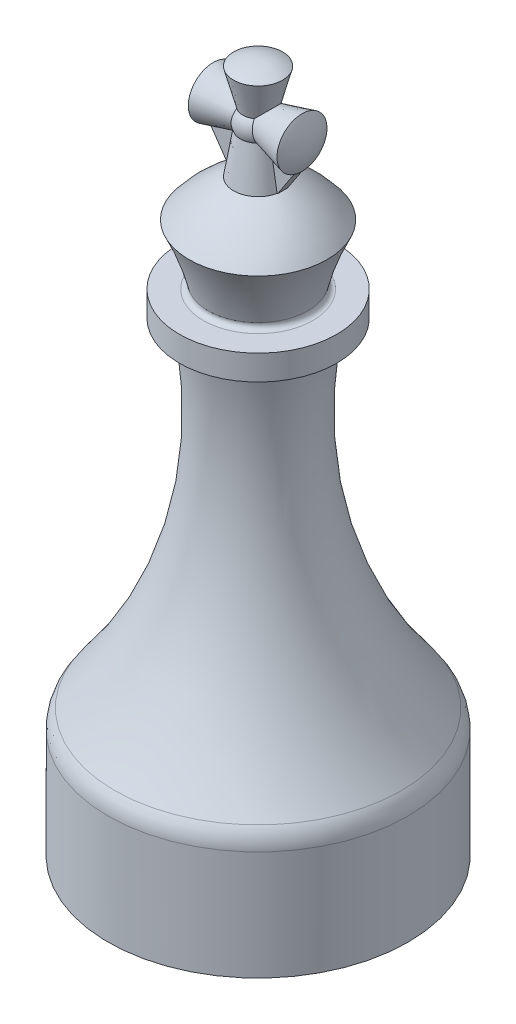
SolidWorks part; units mm, degrees
other "Camera1"
ref_plane "Front Plane" through (0, 0, 0) normal (0, 0, 1) x (1, 0, 0)
ref_plane "Top Plane" through (0, 0, 0) normal (0, 1, 0) x (1, 0, 0)
ref_plane "Right Plane" through (0, 0, 0) normal (1, 0, 0) x (0, 0, -1)
sketch "Sketch3" plane through (0, 0, 0) normal (0, 0, 1) x (1, 0, 0)
  line L0 (31.0622, 0) -> (31.0622, 75)
  line L1 (31.0622, 75) -> (-18.2567, 75)
  line L2 (0, 0) -> (31.0622, 0) construction
  dimension "D1" = 75
sketch "Sketch1" plane through (0, 0, 0) normal (0, 0, 1) x (1, 0, 0)
  line L9 (15, 0) -> (15, 12)
  line L10 (9.5, 0) -> (9.5, 12)
  line L11 (9.5, 12) -> (15, 12) construction
  line L12 (7.6716, 18.1769) -> (0, 30)
  line L13 (0, 69) -> (0, 30)
  line L14 (6, 45.6431) -> (7.8651, 46.5776)
  line L15 (7.8651, 46.5776) -> (7.8651, 49.0804)
  line L16 (0, 0) -> (15, 0)
  line L17 (7.8651, 49.0804) -> (4.858, 49.0804)
  line L18 (2.4501, 58.8041) -> (1.7709, 62.9502)
  line L19 (1.5275, 64.8974) -> (2.4501, 68.3922)
  line L21 (0, 0) -> (0, 69) construction
  arc A5 (9.5, 12) -> (7.6716, 18.1769) centre (-1.8479, 12) ccw
  arc A6 (4.858, 49.0804) -> (6.907, 55.0794) centre (28.9648, 44.1961) cw
  arc A7 (2.4501, 58.8041) -> (6.907, 55.0794) centre (-3.7241, 46.8873) cw
  arc A8 (1.5275, 64.8974) -> (1.7709, 62.9502) centre (0.106, 63.7309) cw
  arc A9 (0, 69) -> (2.4501, 68.3922) centre (0.0489, 63.9548) cw
  arc A10 (15, 12) -> (6, 45.6431) centre (46.1966, 38.3709) cw
  point P26 (6.3616, 49.0804)
  dimension "D4" = 30
  dimension "D1" = 15
  dimension "D2" = 12
  dimension "D3" = 9.5
  dimension "D8" = 69
revolve "Revolve1" add sketch "Sketch1" angle 360 about L21
fillet "Fillet1" radius 3 1 edges at (15, 12, 0)
fillet "Fillet2" radius 0.5 1 edges at (4.858, 49.0804, 0)
sketch "Sketch2" plane through (0, 0, 0) normal (0, 0, 1) x (1, 0, 0)
  line L24 (-5.0944, 63.9548) -> (4.9965, 63.9548)
  line L30 (4.3885, 61.4557) -> (-0.0489, 62.6272)
  line L31 (-0.0489, 62.6272) -> (-0.0489, 63.9548) construction
  line L32 (-4.4864, 61.4557) -> (-0.0489, 62.6272)
  arc A2 (4.9965, 63.9548) -> (4.3885, 61.4557) centre (-0.3969, 63.9434) cw
  arc A3 (-5.0944, 63.9548) -> (-4.4864, 61.4557) centre (0.299, 63.9434) ccw
revolve "Revolve2" add sketch "Sketch2" angle 360 about L24
sketch "Sketch4" plane through (0, 0, 0) normal (0, 0, 1) x (1, 0, 0)
  line L0 (-4.4864, 61.7486) -> (-0.013, 62.9502)
  line L1 (4.3885, 61.7486) -> (-0.013, 62.9502)
  line L2 (-4.4864, 61.7486) -> (-2.4501, 58.8041)
  line L3 (-2.4501, 58.8041) -> (2.4501, 58.8041)
  line L4 (2.4501, 58.8041) -> (4.3885, 61.7486)
  line L5 (1.1873, 62.9502) -> (-1.2133, 62.9502) construction
  line L6 (4.3885, 66.4538) -> (4.3885, 61.4557) construction
  line L7 (-4.4864, 66.4538) -> (-4.4864, 61.4557) construction
extrude "Boss-Extrude2" add sketch "Sketch4" along normal mid plane 1
